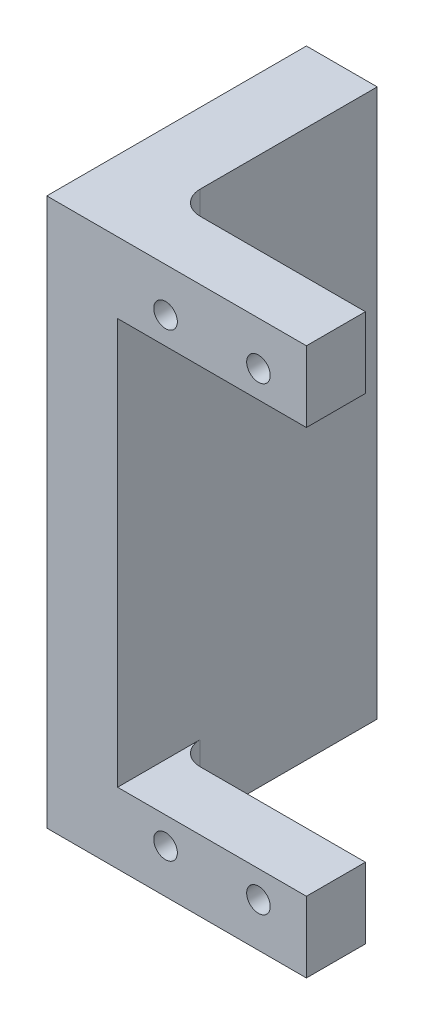
SolidWorks part; units mm, degrees
material "PET"
ref_plane "Front Plane" through (0, 0, 0) normal (0, 0, 1) x (1, 0, 0)
ref_plane "Top Plane" through (0, 0, 0) normal (0, 1, 0) x (1, 0, 0)
ref_plane "Right Plane" through (0, 0, 0) normal (1, 0, 0) x (0, 0, -1)
sketch "Sketch1" plane through (0, 0, 0) normal (0, 0, 1) x (1, 0, 0)
  line L0 (5.16, -2.9058) -> (15.16, -2.9058) construction
  line L1 (0, 0) -> (20.32, 0)
  line L2 (0, 0) -> (0, 43.688)
  line L3 (0, 43.688) -> (20.32, 43.688)
  line L4 (20.32, 0) -> (20.32, 43.688) construction
  line L5 (15.16, -2.9058) -> (15.16, 46.5938) construction
  line L6 (15.16, 46.5938) -> (5.16, 46.5938) construction
  line L7 (5.16, 46.5938) -> (5.16, -2.9058) construction
  line L8 (15.16, 21.844) -> (20.32, 21.844) construction
  line L9 (10.16, 0) -> (10.16, -2.9058) construction
  line L10 (20.32, 0) -> (20.32, -7.62)
  line L11 (20.32, -7.62) -> (-7.62, -7.62)
  line L12 (-7.62, -7.62) -> (-7.62, 51.308)
  line L13 (-7.62, 51.308) -> (20.32, 51.308)
  line L14 (20.32, 51.308) -> (20.32, 43.688)
  circle A0 centre (5.16, 46.5938) radius 1.27
  circle A1 centre (15.16, 46.5938) radius 1.27
  circle A2 centre (5.16, -2.9058) radius 1.27
  circle A3 centre (15.16, -2.9058) radius 1.27
  dimension "D5" = 2.54
  dimension "D1" = 43.688
  dimension "D2" = 20.32
  dimension "D3" = 49.4995
  dimension "D4" = 10
  dimension "D6" = 7.62
  dimension "D7" = 7.62
extrude "Boss-Extrude1" add sketch "Sketch1" along normal blind 6.35
sketch "Sketch2" plane through (0, 0, 0) normal (0, 0, -1) x (-1, 0, 0)
  line L0 (7.62, -7.62) -> (-20.32, -7.62) construction
  line L1 (7.62, 51.308) -> (0, 51.308)
  line L2 (7.62, 51.308) -> (7.62, -7.62)
  line L3 (7.62, -7.62) -> (0, -7.62)
  line L4 (0, 51.308) -> (0, -7.62)
extrude "Boss-Extrude2" add sketch "Sketch2" along normal offset from surface (21.59 mm away) 27.94 up to face at (8.255, 21.844, 6.35)
sketch "Sketch3" plane through (0, 0, -21.59) normal (0, 0, -1) x (-1, 0, 0)
  line L1 (7.62, -7.62) -> (7.62, 51.308) construction
  line L3 (13.97, 5.969) -> (13.97, 37.719) construction
  line L4 (13.97, 21.844) -> (7.62, 21.844) construction
  line L5 (13.97, 42.799) -> (7.62, 42.799)
  line L6 (13.97, 32.639) -> (7.62, 32.639)
  line L7 (13.97, 11.049) -> (7.62, 11.049)
  line L8 (13.97, 0.889) -> (7.62, 0.889)
  line L9 (7.62, 0.889) -> (7.62, 11.049)
  line L10 (7.62, 32.639) -> (7.62, 42.799)
  circle A0 centre (13.97, 37.719) radius 1.905
  circle A1 centre (13.97, 5.969) radius 1.905
  arc A2 (13.97, 32.639) -> (13.97, 42.799) centre (13.97, 37.719) ccw
  arc A3 (13.97, 0.889) -> (13.97, 11.049) centre (13.97, 5.969) ccw
  dimension "D1" = 3.81
  dimension "D2" = 3.81
  dimension "D6" = 3.175
  dimension "D7" = 3.175
  dimension "D3" = 6.35
  dimension "D5" = 31.75
extrude "Boss-Extrude3" add sketch "Sketch3" against normal blind 3.81
fillet "Fillet1" radius 2.54 8 edges at (0, 47.498, 0) (0, -3.81, 0) (-7.62, 42.799, -19.685) (-7.62, 32.639, -19.685) (-7.62, 11.049, -19.685) (-7.62, 0.889, -19.685) (-7.62, 5.969, -17.78) (-7.62, 37.719, -17.78)
